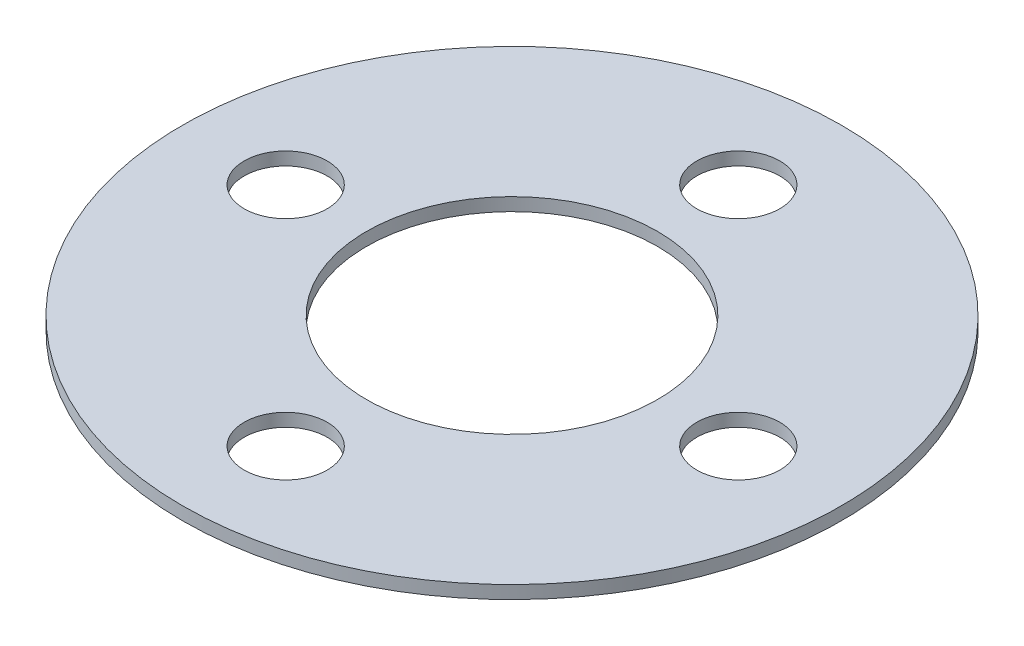
SolidWorks part; units mm, degrees
ref_plane "Front Plane" through (0, 0, 0) normal (0, 0, 1) x (1, 0, 0)
ref_plane "Top Plane" through (0, 0, 0) normal (0, 1, 0) x (1, 0, 0)
ref_plane "Right Plane" through (0, 0, 0) normal (1, 0, 0) x (0, 0, -1)
sketch "Sketch1" plane through (0, 0, 0) normal (0, 1, 0) x (1, 0, 0)
  circle A0 centre (0, 0) radius 21.844
  circle A1 centre (0, 15) radius 2.75
  circle A2 centre (15, 0) radius 2.75
  circle A3 centre (0, -15) radius 2.75
  circle A4 centre (-15, 0) radius 2.75
  point P14 (0, 0)
  dimension "D1" = 43.688
  dimension "D2" = 5.5
  dimension "D3" = 15
  dimension "D4" = 4
extrude "Boss-Extrude1" add sketch "Sketch1" along normal blind 0.8636
sketch "Sketch2" plane through (0, 0, 0) normal (0, -1, 0) x (1, 0, 0)
  circle A0 centre (0, 0) radius 9.652
extrude "Cut-Extrude1" cut sketch "Sketch2" against normal blind 0.8636
